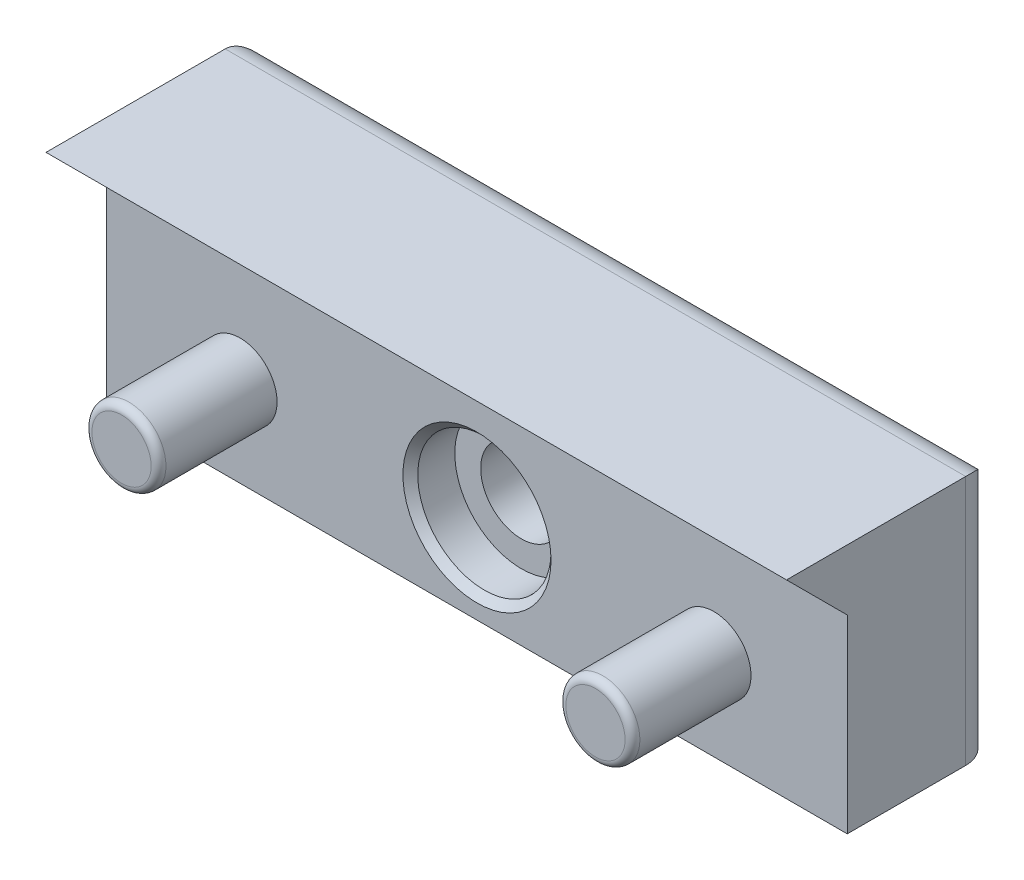
SolidWorks part; units mm, degrees
ref_plane "Front" through (0, 0, 0) normal (0, 0, 1) x (1, 0, 0)
ref_plane "Top" through (0, 0, 0) normal (0, 1, 0) x (1, 0, 0)
ref_plane "Right" through (0, 0, 0) normal (1, 0, 0) x (0, 0, -1)
sketch "Sketch1" plane through (0, 0, 0) normal (0, 0, 1) x (1, 0, 0)
  line L1 (25, -8) -> (-25, -8)
  line L2 (25, -8) -> (25, 8)
  line L3 (25, 8) -> (-25, 8)
  line L4 (-25, -8) -> (-25, 8)
  line L5 (25, -8) -> (-25, 8) construction
  line L6 (25, 8) -> (-25, -8) construction
  point P0 (0, 0)
  dimension "D1" = 50
  dimension "D2" = 16
extrude "Boss-Extrude1" add sketch "Sketch1" along normal blind 10
sketch "Sketch2" plane through (0, 0, 10) normal (0, 0, 1) x (1, 0, 0)
  circle A0 centre (0, 0) radius 2.75
  dimension "D1" = 5.5
extrude "Cut-Extrude1" cut sketch "Sketch2" against normal through all
sketch "Sketch3" plane through (0, 0, 10) normal (0, 0, 1) x (1, 0, 0)
  line L0 (-25, 8) -> (-25, -8) construction
  line L1 (25, -8) -> (25, 8) construction
  circle A0 centre (-16, 0) radius 2.5
  circle A1 centre (16, 0) radius 2.5
  dimension "D3" = 5
  dimension "D4" = 5
  dimension "D1" = 9
  dimension "D2" = 9
extrude "Boss-Extrude2" add sketch "Sketch3" along normal blind 8
fillet "Fillet1" radius 0.5 2 edges at (18.5, 0, 18) (-13.5, 0, 18)
sketch "Sketch4" plane through (0, -8, 0) normal (0, -1, 0) x (-1, 0, 0)
  line L1 (-25, -10) -> (25, -10)
  line L2 (-25, -10) -> (-25, 0)
  line L3 (-25, 0) -> (25, 0)
  line L4 (25, -10) -> (25, 0)
extrude "Cut-Extrude2" cut sketch "Sketch4" against normal blind 2
sketch "Sketch5" plane through (0, 8, 0) normal (0, 1, 0) x (1, 0, 0)
  line L1 (25, -10) -> (-25, -10)
  line L2 (25, -10) -> (25, 0)
  line L3 (25, 0) -> (-25, 0)
  line L4 (-25, -10) -> (-25, 0)
extrude "Boss-Extrude3" add sketch "Sketch5" along normal blind 2.9
sketch "Sketch6" plane through (25, 0, 0) normal (1, 0, 0) x (0, 0, -1)
  line L0 (-14.1, 10.9) -> (-10, 6.8)
  line L1 (-10, 10.9) -> (-14.1, 10.9)
  line L2 (-10, 10.9) -> (-10, 6.8)
  dimension "D1" = 4.1
  dimension "D2" = 4.1
extrude "Boss-Extrude4" add sketch "Sketch6" against normal through all
fillet "Fillet2" radius 2 3 edges at (0, 10.9, 0) (-25, 2.45, 0) (25, 2.45, 0)
sketch "Sketch7" plane through (0, 0, 10) normal (0, 0, 1) x (1, 0, 0)
  circle A0 centre (0, 0) radius 4.5
  dimension "D1" = 9
extrude "Cut-Extrude3" cut sketch "Sketch7" against normal blind 3
chamfer "Chamfer1" distance 0.5 angle 45 1 edges at (4.5, 0, 10)
